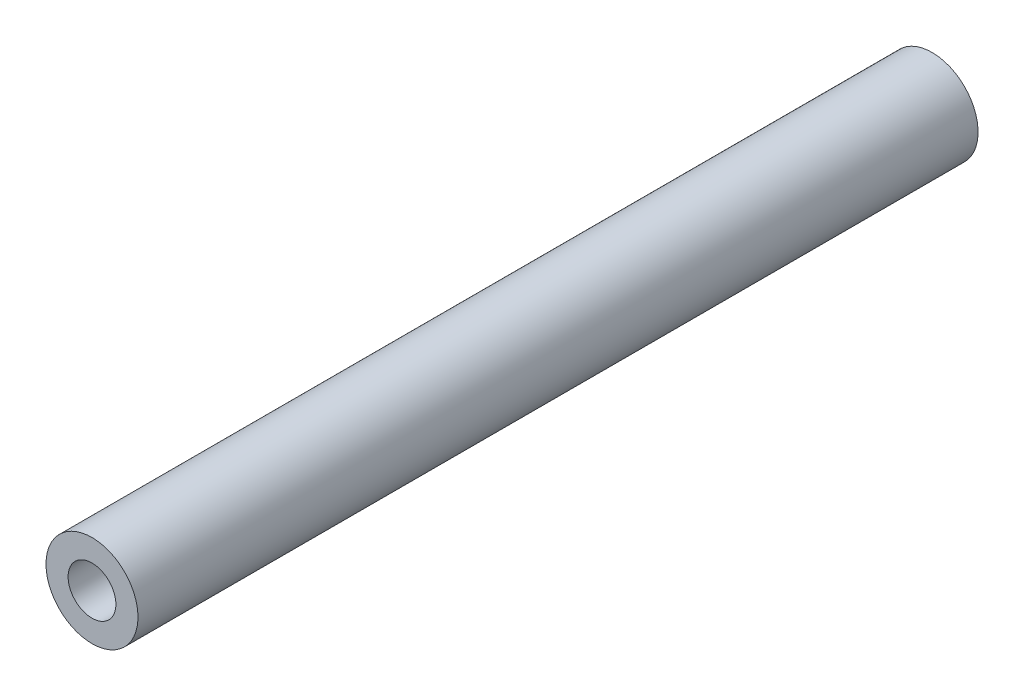
SolidWorks part; units mm, degrees
ref_plane "Front Plane" through (0, 0, 0) normal (0, 0, 1) x (1, 0, 0)
ref_plane "Top Plane" through (0, 0, 0) normal (0, 1, 0) x (1, 0, 0)
ref_plane "Right Plane" through (0, 0, 0) normal (1, 0, 0) x (0, 0, -1)
sketch "Sketch1" plane through (0, 0, 0) normal (0, 0, 1) x (1, 0, 0)
  circle A0 centre (0, 0) radius 3.175
  dimension "D1" = 6.35
extrude "Boss-Extrude1" add sketch "Sketch1" along normal mid plane 58
sketch "Sketch2" plane through (0, 0, 29) normal (0, 0, 1) x (1, 0, 0)
  point P0 (0, 0)
hole_wizard "M4x0.7 Tapped Hole1" positions "Sketch4" profile "Sketch3" tap size "M4x0.7" standard "ANSI Metric"
sketch "Sketch4" plane through (0, 0, 29) normal (0, 0, 1) x (1, 0, 0)
  point P0 (0, 0)
sketch "Sketch3" plane through (0, 0, 29) normal (1, 0, 0) x (0, -1, 0)
  line L0 (0, 0) -> (0, 18.0094)
  line L1 (0, 18.0094) -> (1.65, 17.018)
  line L2 (1.65, 17.018) -> (1.65, 0)
  line L5 (1.65, 0) -> (0, 0)
  line L10 (0, 18.0094) -> (-1.65, 17.018) construction
  line L11 (0, -6.35) -> (0, 107.95) construction
  dimension "Tap Drill Dia." = 3.3
  dimension "Tap Drill Depth" = 17.018
  dimension "Drill Angle" = 118
cosmetic thread "Hole Thread1" parameters "D1"=14.986, "D2"=4
mirror "Mirror1" about plane through (0, 0, 0) normal (0, 0, 1) of "M4x0.7 Tapped Hole1"
